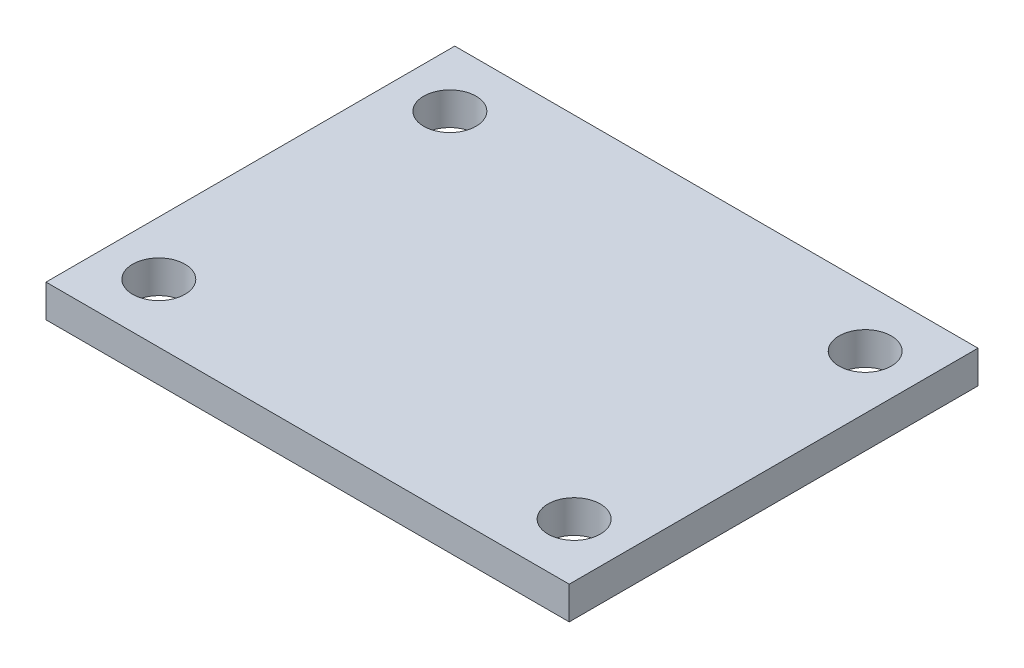
SolidWorks part; units mm, degrees
ref_plane "Front Plane" through (0, 0, 0) normal (0, 0, 1) x (1, 0, 0)
ref_plane "Top Plane" through (0, 0, 0) normal (0, 1, 0) x (1, 0, 0)
ref_plane "Right Plane" through (0, 0, 0) normal (1, 0, 0) x (0, 0, -1)
sketch "Sketch1" plane through (0, 0, 0) normal (0, 1, 0) x (1, 0, 0)
  line L1 (-16, 12.5) -> (16, 12.5)
  line L2 (-16, 12.5) -> (-16, -12.5)
  line L3 (-16, -12.5) -> (16, -12.5)
  line L4 (16, 12.5) -> (16, -12.5)
  line L5 (-16, 12.5) -> (16, -12.5) construction
  line L6 (-16, -12.5) -> (16, 12.5) construction
  point P0 (0, 0)
  dimension "D1" = 25
  dimension "D2" = 32
extrude "Boss-Extrude1" add sketch "Sketch1" along normal blind 2 contours L1 L4 L3 L2
sketch "Sketch2" plane through (0, 0, 0) normal (0, 1, 0) x (1, 0, 0)
  line L0 (-12.7, 8.9) -> (-12.7, -8.9) construction
  line L1 (-12.7, -8.9) -> (12.7, -8.9) construction
  circle A0 centre (-12.7, 8.9) radius 1.6
  circle A1 centre (-12.7, -8.9) radius 1.6
  circle A2 centre (12.7, 8.9) radius 1.6
  circle A3 centre (12.7, -8.9) radius 1.6
  point P8 (-12.7, 0)
  point P9 (0, -8.9)
  dimension "D1" = 17.8
  dimension "D2" = 3.2
  dimension "D3" = 25.4
extrude "Cut-Extrude1" cut sketch "Sketch2" along normal through all
